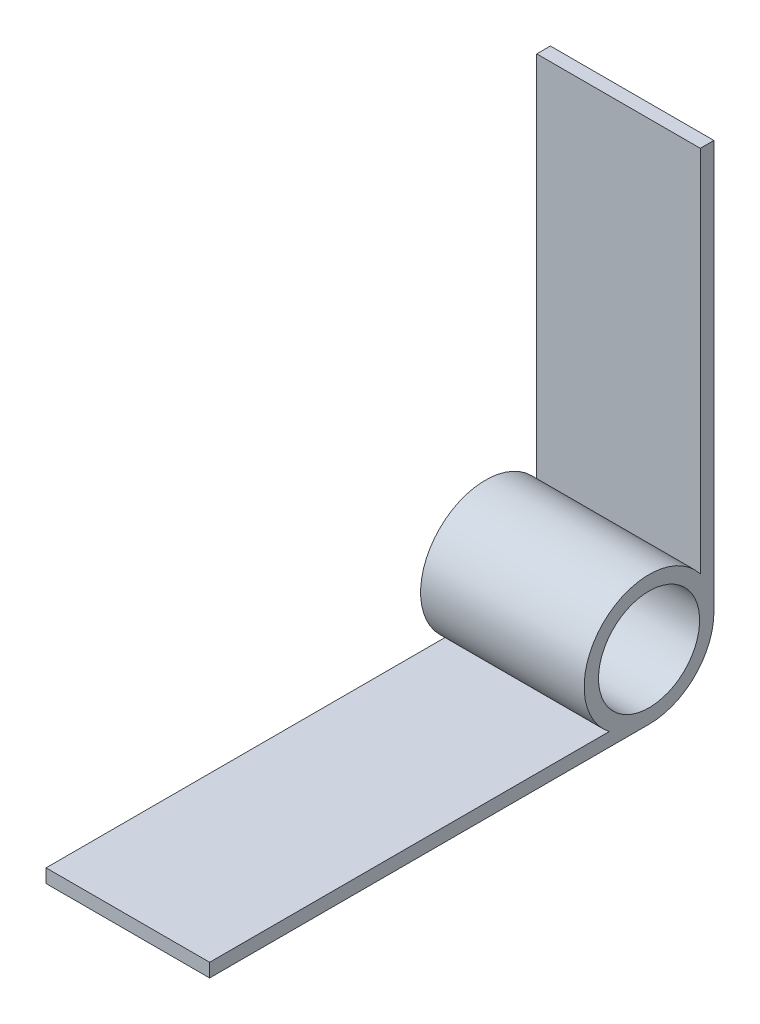
SolidWorks part; units mm, degrees
ref_plane "Front Plane" through (0, 0, 0) normal (0, 0, 1) x (1, 0, 0)
ref_plane "Top Plane" through (0, 0, 0) normal (0, 1, 0) x (1, 0, 0)
ref_plane "Right Plane" through (0, 0, 0) normal (1, 0, 0) x (0, 0, -1)
sketch "Sketch1" plane through (0, 0, 0) normal (1, 0, 0) x (0, 0, -1)
  line L0 (3.0226, 0) -> (3.0226, 19.0246)
  line L1 (3.0226, 19.0246) -> (2.3876, 19.0246)
  line L2 (2.3876, 19.0246) -> (2.3876, 1.8535)
  line L3 (0, -3.0226) -> (-20.4724, -3.0226)
  line L4 (-20.4724, -3.0226) -> (-20.4724, -2.3876)
  line L5 (-20.4724, -2.3876) -> (-1.8535, -2.3876)
  arc A0 (0, -3.0226) -> (3.0226, 0) centre (0, 0) ccw
  arc A1 (2.3876, 1.8535) -> (-1.8535, -2.3876) centre (0, 0) ccw
  circle A2 centre (0, 0) radius 2.3559
  point P1 (-20.4724, -2.7051)
  dimension "D1" = 22.0472
  dimension "D5" = 3.0226
  dimension "D2" = 23.495
  dimension "D3" = 0.635
  dimension "D4" = 0.635
extrude "Boss-Extrude1" add sketch "Sketch1" along normal blind 7.62
